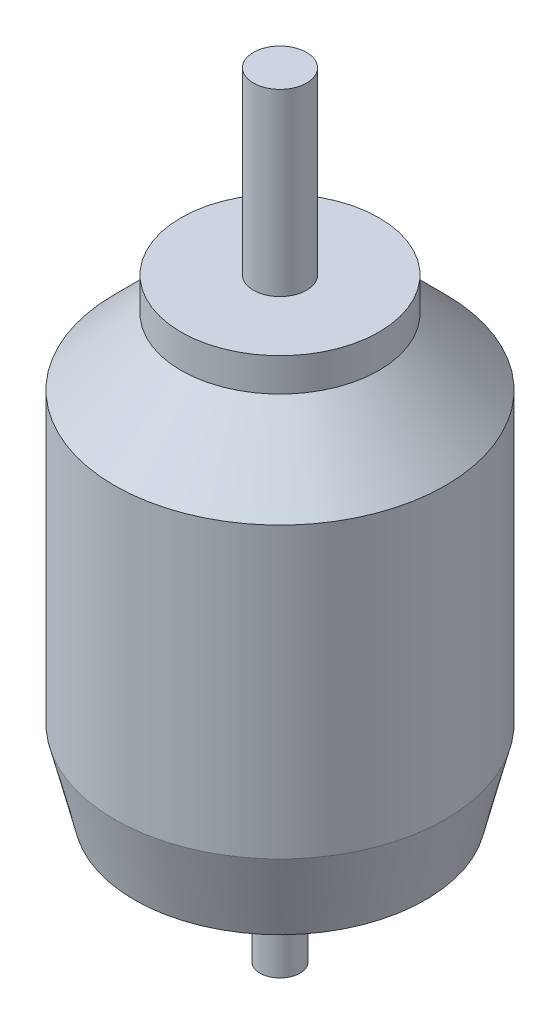
SolidWorks part; units mm, degrees
ref_plane "Front Plane" through (0, 0, 0) normal (0, 0, 1) x (1, 0, 0)
ref_plane "Top Plane" through (0, 0, 0) normal (0, 1, 0) x (1, 0, 0)
ref_plane "Right Plane" through (0, 0, 0) normal (1, 0, 0) x (0, 0, -1)
sketch "Sketch2" plane through (0, 0, 0) normal (0, 1, 0) x (1, 0, 0)
  circle A0 centre (0, 0) radius 3
  dimension "D1" = 6
extrude "Boss-Extrude3" add sketch "Sketch2" along normal blind 18.5
sketch "Sketch3" plane through (0, 18.5, 0) normal (0, 1, 0) x (1, 0, 0)
  circle A0 centre (0, 0) radius 6
extrude "Boss-Extrude5" add sketch "Sketch3" along normal blind 0.5 contours A0
sketch "Sketch5" plane through (0, 19, 0) normal (0, 1, 0) x (1, 0, 0)
  circle A0 centre (0, 0) radius 24.9
  dimension "D1" = 49.8
extrude "Boss-Extrude6" add sketch "Sketch5" along normal blind 65.5
sketch "Sketch6" plane through (0, 84.5, 0) normal (0, 1, 0) x (1, 0, 0)
  circle A0 centre (0, 0) radius 4
  dimension "D1" = 8
extrude "Boss-Extrude7" add sketch "Sketch6" along normal blind 32
chamfer "Chamfer1" distance 3 distance2 12 1 edges at (0, 19, 24.9)
chamfer "Chamfer2" distance 10 angle 45 1 edges at (0, 84.5, 24.9)
sketch "Sketch7" plane through (0, 84.5, 0) normal (0, 1, 0) x (1, 0, 0)
  circle A0 centre (0, 0) radius 14.9
  circle A1 centre (0, 0) radius 14.9 construction
extrude "Boss-Extrude8" add sketch "Sketch7" along normal blind 5
hole_wizard "M4x0.7 Tapped Hole1" positions "Sketch13" profile "Sketch12" tap size "M4x0.7" standard "ANSI Metric"
sketch "Sketch13" plane through (0, 19, 0) normal (0, -1, 0) x (-1, 0, 0)
  line L0 (-10.6066, -10.6066) -> (10.6066, 10.6066) construction
  line L2 (-10.6066, 10.6066) -> (10.6066, -10.6066) construction
  line L4 (0, 0) -> (15, 0) construction
  circle A0 centre (0, 0) radius 15 construction
  point P0 (-10.6066, 10.6066)
  point P2 (10.6066, -10.6066)
  point P4 (10.6066, 10.6066)
  point P6 (-10.6066, -10.6066)
  point P30 (10.6066, 10.6066)
  point P31 (10.6066, -10.6066)
  point P32 (-10.6066, -10.6066)
  point P33 (-10.6066, 10.6066)
  dimension "D1" = 45
  dimension "D2" = 30
sketch "Sketch12" plane through (10.6066, 19, -10.6066) normal (1, 0, 0) x (0, 0, -1)
  line L0 (0, 0) -> (0, 11.5)
  line L1 (0, 11.5) -> (1.65, 10.5086)
  line L2 (1.65, 10.5086) -> (1.65, 0.375)
  line L3 (1.65, 0.375) -> (2.025, 0)
  line L5 (2.025, 0) -> (0, 0)
  line L6 (-1.65, 0.375) -> (-2.025, 0) construction
  line L10 (0, 11.5) -> (-1.65, 10.5086) construction
  line L11 (0, -6.35) -> (0, 107.95) construction
  dimension "Tap Drill Dia." = 3.3
  dimension "Tap Drill Depth" = 11.5
  dimension "Near C'Sink Dia." = 4.05
  dimension "Near C'Sink Angle" = 90
  dimension "Drill Angle" = 118
cosmetic thread "Hole Thread1" parameters "D1"=8, "D2"=4
cosmetic thread "Hole Thread2" parameters "D1"=8, "D2"=4
cosmetic thread "Hole Thread3" parameters "D1"=8, "D2"=4
cosmetic thread "Hole Thread4" parameters "D1"=8, "D2"=4
